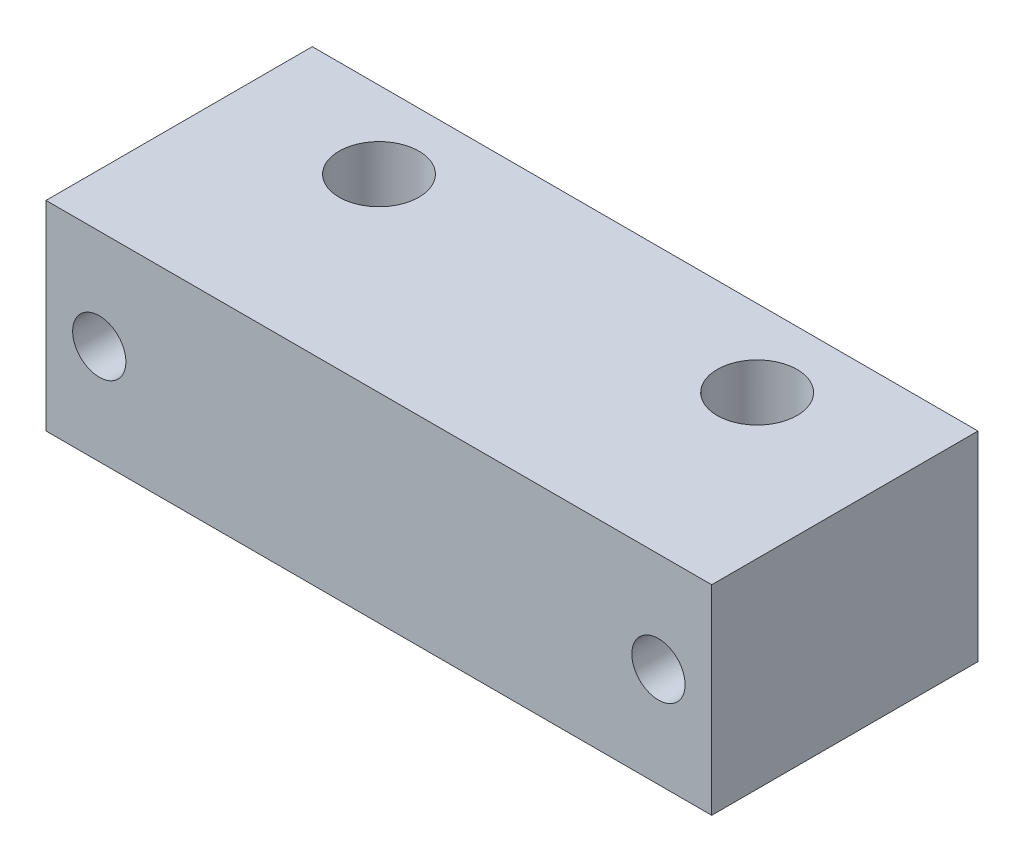
SolidWorks part; units mm, degrees
ref_plane "Plano frontal" through (0, 0, 0) normal (0, 0, 1) x (1, 0, 0)
ref_plane "Plano superior" through (0, 0, 0) normal (0, 1, 0) x (1, 0, 0)
ref_plane "Plano direito" through (0, 0, 0) normal (1, 0, 0) x (0, 0, -1)
sketch "Esboço1" plane through (0, 0, 0) normal (0, 1, 0) x (1, 0, 0)
  line L10 (49.4415, 21) -> (-0.5585, 21)
  line L19 (-0.5585, 21) -> (-0.5585, 41)
  line L20 (-0.5585, 41) -> (49.4415, 41)
  line L21 (49.4415, 41) -> (49.4415, 21)
  circle A1 centre (10.2415, 35.2108) radius 3
  circle A2 centre (38.6415, 35.2108) radius 3
  dimension "D4" = 6
  dimension "D8" = 6
  dimension "D2" = 50
  dimension "D7" = 14.2108
extrude "Ressalto-extrusão1" add sketch "Esboço1" along normal blind 15
sketch "Esboço2" plane through (0, 0, -41) normal (0, 0, -1) x (-1, 0, 0)
  line L0 (-49.4415, 15) -> (-49.4415, 0) construction
  line L1 (0.5585, 15) -> (0.5585, 0) construction
  line L2 (0.5585, 0) -> (-49.4415, 0) construction
  circle A0 centre (-3.4415, 7.5) radius 2
  circle A1 centre (-45.4415, 7.5) radius 2
  dimension "D1" = 4
  dimension "D2" = 4
  dimension "D3" = 4
  dimension "D4" = 4
  dimension "D5" = 7.5
  dimension "D6" = 7.5
extrude "Corte-extrusão1" cut sketch "Esboço2" against normal through all
sketch "Esboço3" plane through (0, 0, -41) normal (0, 0, -1) x (-1, 0, 0)
  line L2 (-49.4415, 15) -> (-49.4415, 0) construction
  line L3 (0.5585, 15) -> (0.5585, 0) construction
  circle A2 centre (-10.2415, 7.5) radius 2
  circle A3 centre (-38.6415, 7.5) radius 2
  dimension "D3" = 4
  dimension "D4" = 4
  dimension "D1" = 10.8
  dimension "D2" = 10.8
extrude "Corte-extrusão2" cut sketch "Esboço3" against normal blind 4
